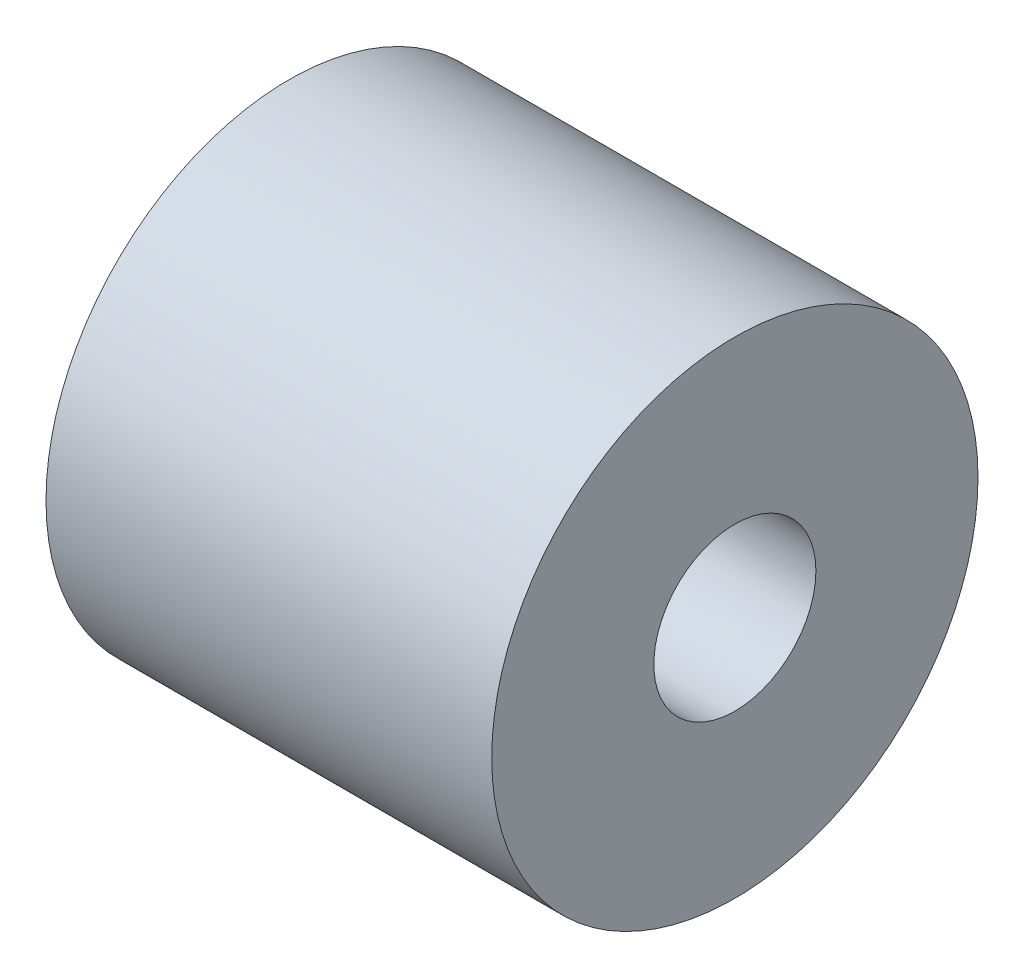
SolidWorks part; units mm, degrees
ref_plane "Plan de face" through (0, 0, 0) normal (0, 0, 1) x (1, 0, 0)
ref_plane "Plan de dessus" through (0, 0, 0) normal (0, 1, 0) x (1, 0, 0)
ref_plane "Plan de droite" through (0, 0, 0) normal (1, 0, 0) x (0, 0, -1)
sketch "Esquisse1" plane through (0, 0, 0) normal (1, 0, 0) x (0, 0, -1)
  arc A0 (2.9773, 0.3683) -> (2.9271, 0.6573) centre (0, 0) ccw
  arc A1 (2.1922, 2.048) -> (1.9817, 2.2523) centre (0, 0) ccw
  arc A2 (0.5698, 2.9454) -> (0.2794, 2.987) centre (0, 0) ccw
  arc A3 (-1.2703, 2.7178) -> (-1.5297, 2.5807) centre (0, 0) ccw
  arc A4 (-2.6252, 1.4521) -> (-2.7544, 1.1887) centre (0, 0) ccw
  arc A5 (-2.9773, -0.3683) -> (-2.9271, -0.6573) centre (0, 0) ccw
  arc A6 (-2.1922, -2.048) -> (-1.9817, -2.2523) centre (0, 0) ccw
  arc A7 (-0.5698, -2.9454) -> (-0.2794, -2.987) centre (0, 0) ccw
  arc A8 (1.2703, -2.7178) -> (1.5297, -2.5807) centre (0, 0) ccw
  arc A9 (2.6252, -1.4521) -> (2.7544, -1.1887) centre (0, 0) ccw
  arc A10 (1.8368, -0.3764) -> (1.8687, -0.154) centre (0, 0) ccw
  arc A11 (1.7073, 0.7751) -> (1.6023, 0.9738) centre (0, 0) ccw
  arc A12 (0.9256, 1.6306) -> (0.7239, 1.7296) centre (0, 0) ccw
  arc A13 (-0.2096, 1.8632) -> (-0.431, 1.8248) centre (0, 0) ccw
  arc A14 (-1.2648, 1.3842) -> (-1.4213, 1.2229) centre (0, 0) ccw
  arc A15 (-1.8368, 0.3764) -> (-1.8687, 0.154) centre (0, 0) ccw
  arc A16 (-1.7073, -0.7751) -> (-1.6023, -0.9738) centre (0, 0) ccw
  arc A17 (-0.9256, -1.6306) -> (-0.7239, -1.7296) centre (0, 0) ccw
  arc A18 (0.2096, -1.8632) -> (0.431, -1.8248) centre (0, 0) ccw
  arc A19 (1.2648, -1.3842) -> (1.4213, -1.2229) centre (0, 0) ccw
  circle A20 centre (0, 0) radius 1
  spline S0 degree 3 poles (2.349, 0) (2.3611, 0) (2.4126, 0.0085) (2.4945, 0.0326) (2.6584, 0.1065) (2.823, 0.2207) (2.9394, 0.3292) (2.9773, 0.3683) knots 0 0 0 0 0.036251 0.155621 0.255291 0.575255 0.744085 0.744085 0.744085 0.744085
  spline S1 degree 3 poles (2.2114, 0.7921) (2.2228, 0.7962) (2.2741, 0.8056) (2.3594, 0.8105) (2.5386, 0.7962) (2.7321, 0.7442) (2.8782, 0.6813) (2.9271, 0.6573) knots 0 0 0 0 0.036251 0.155621 0.255291 0.575255 0.744085 0.744085 0.744085 0.744085
  spline S2 degree 3 poles (1.9004, 1.3807) (1.9102, 1.3878) (1.9469, 1.4249) (1.9989, 1.4926) (2.0881, 1.6487) (2.1541, 1.8379) (2.1845, 1.9941) (2.1922, 2.048) knots 0 0 0 0 0.036251 0.155621 0.255291 0.575255 0.744085 0.744085 0.744085 0.744085
  spline S3 degree 3 poles (1.3235, 1.9407) (1.3303, 1.9507) (1.3663, 1.9885) (1.4324, 2.0425) (1.5858, 2.1363) (1.7728, 2.2079) (1.9281, 2.243) (1.9817, 2.2523) knots 0 0 0 0 0.036251 0.155621 0.255291 0.575255 0.744085 0.744085 0.744085 0.744085
  spline S4 degree 3 poles (0.7259, 2.234) (0.7296, 2.2455) (0.7375, 2.2971) (0.7398, 2.3825) (0.7202, 2.5612) (0.6625, 2.753) (0.5952, 2.8973) (0.5698, 2.9454) knots 0 0 0 0 0.036251 0.155621 0.255291 0.575255 0.744085 0.744085 0.744085 0.744085
  spline S5 degree 3 poles (-0.07, 2.348) (-0.0704, 2.36) (-0.0634, 2.4118) (-0.0417, 2.4943) (0.0272, 2.6604) (0.1365, 2.8283) (0.2415, 2.9479) (0.2794, 2.987) knots 0 0 0 0 0.036251 0.155621 0.255291 0.575255 0.744085 0.744085 0.744085 0.744085
  spline S6 degree 3 poles (-0.7259, 2.234) (-0.7296, 2.2455) (-0.7536, 2.2919) (-0.8019, 2.3623) (-0.9228, 2.4954) (-1.0823, 2.6166) (-1.2215, 2.6938) (-1.2703, 2.7178) knots 0 0 0 0 0.036251 0.155621 0.255291 0.575255 0.744085 0.744085 0.744085 0.744085
  spline S7 degree 3 poles (-1.4367, 1.8584) (-1.4441, 1.8679) (-1.4689, 1.9139) (-1.4999, 1.9934) (-1.5417, 2.1683) (-1.552, 2.3684) (-1.5374, 2.5268) (-1.5297, 2.5807) knots 0 0 0 0 0.036251 0.155621 0.255291 0.575255 0.744085 0.744085 0.744085 0.744085
  spline S8 degree 3 poles (-1.9004, 1.3807) (-1.9102, 1.3878) (-1.9568, 1.4112) (-2.0373, 1.4398) (-2.2133, 1.4764) (-2.4136, 1.4808) (-2.5715, 1.4614) (-2.6252, 1.4521) knots 0 0 0 0 0.036251 0.155621 0.255291 0.575255 0.744085 0.744085 0.744085 0.744085
  spline S9 degree 3 poles (-2.2547, 0.659) (-2.2663, 0.6624) (-2.3133, 0.6849) (-2.3852, 0.7311) (-2.5218, 0.848) (-2.6477, 1.0038) (-2.729, 1.1406) (-2.7544, 1.1887) knots 0 0 0 0 0.036251 0.155621 0.255291 0.575255 0.744085 0.744085 0.744085 0.744085
  spline S10 degree 3 poles (-2.349, 0) (-2.3611, 0) (-2.4126, -0.0085) (-2.4945, -0.0326) (-2.6584, -0.1065) (-2.823, -0.2207) (-2.9394, -0.3292) (-2.9773, -0.3683) knots 0 0 0 0 0.036251 0.155621 0.255291 0.575255 0.744085 0.744085 0.744085 0.744085
  spline S11 degree 3 poles (-2.2114, -0.7921) (-2.2228, -0.7962) (-2.2741, -0.8056) (-2.3594, -0.8105) (-2.5386, -0.7962) (-2.7321, -0.7442) (-2.8782, -0.6813) (-2.9271, -0.6573) knots 0 0 0 0 0.036251 0.155621 0.255291 0.575255 0.744085 0.744085 0.744085 0.744085
  spline S12 degree 3 poles (-1.9004, -1.3807) (-1.9102, -1.3878) (-1.9469, -1.4249) (-1.9989, -1.4926) (-2.0881, -1.6487) (-2.1541, -1.8379) (-2.1845, -1.9941) (-2.1922, -2.048) knots 0 0 0 0 0.036251 0.155621 0.255291 0.575255 0.744085 0.744085 0.744085 0.744085
  spline S13 degree 3 poles (-1.3235, -1.9407) (-1.3303, -1.9507) (-1.3663, -1.9885) (-1.4324, -2.0425) (-1.5858, -2.1363) (-1.7728, -2.2079) (-1.9281, -2.243) (-1.9817, -2.2523) knots 0 0 0 0 0.036251 0.155621 0.255291 0.575255 0.744085 0.744085 0.744085 0.744085
  spline S14 degree 3 poles (-0.7259, -2.234) (-0.7296, -2.2455) (-0.7375, -2.2971) (-0.7398, -2.3825) (-0.7202, -2.5612) (-0.6625, -2.753) (-0.5952, -2.8973) (-0.5698, -2.9454) knots 0 0 0 0 0.036251 0.155621 0.255291 0.575255 0.744085 0.744085 0.744085 0.744085
  spline S15 degree 3 poles (0.07, -2.348) (0.0704, -2.36) (0.0634, -2.4118) (0.0417, -2.4943) (-0.0272, -2.6604) (-0.1365, -2.8283) (-0.2415, -2.9479) (-0.2794, -2.987) knots 0 0 0 0 0.036251 0.155621 0.255291 0.575255 0.744085 0.744085 0.744085 0.744085
  spline S16 degree 3 poles (0.7259, -2.234) (0.7296, -2.2455) (0.7536, -2.2919) (0.8019, -2.3623) (0.9228, -2.4954) (1.0823, -2.6166) (1.2215, -2.6938) (1.2703, -2.7178) knots 0 0 0 0 0.036251 0.155621 0.255291 0.575255 0.744085 0.744085 0.744085 0.744085
  spline S17 degree 3 poles (1.4367, -1.8584) (1.4441, -1.8679) (1.4689, -1.9139) (1.4999, -1.9934) (1.5417, -2.1683) (1.552, -2.3684) (1.5374, -2.5268) (1.5297, -2.5807) knots 0 0 0 0 0.036251 0.155621 0.255291 0.575255 0.744085 0.744085 0.744085 0.744085
  spline S18 degree 3 poles (1.9004, -1.3807) (1.9102, -1.3878) (1.9568, -1.4112) (2.0373, -1.4398) (2.2133, -1.4764) (2.4136, -1.4808) (2.5715, -1.4614) (2.6252, -1.4521) knots 0 0 0 0 0.036251 0.155621 0.255291 0.575255 0.744085 0.744085 0.744085 0.744085
  spline S19 degree 3 poles (2.2547, -0.659) (2.2663, -0.6624) (2.3133, -0.6849) (2.3852, -0.7311) (2.5218, -0.848) (2.6477, -1.0038) (2.729, -1.1406) (2.7544, -1.1887) knots 0 0 0 0 0.036251 0.155621 0.255291 0.575255 0.744085 0.744085 0.744085 0.744085
  spline S20 degree 3 poles (2.349, 0) (2.2648, 0) (2.1034, 0.0291) (1.8817, -0.0633) (1.8687, -0.154) knots 0 0 0 0 0.252618 0.527509 0.527509 0.527509 0.527509
  spline S21 degree 3 poles (2.2547, -0.659) (2.1739, -0.6353) (2.0108, -0.618) (1.8238, -0.4671) (1.8368, -0.3764) knots 0 0 0 0 0.252618 0.527509 0.527509 0.527509 0.527509
  spline S22 degree 3 poles (1.9004, 1.3807) (1.8323, 1.3312) (1.6846, 1.2599) (1.5595, 1.0548) (1.6023, 0.9738) knots 0 0 0 0 0.252618 0.527509 0.527509 0.527509 0.527509
  spline S23 degree 3 poles (2.2114, 0.7921) (2.1321, 0.7637) (1.99, 0.682) (1.7501, 0.6941) (1.7073, 0.7751) knots 0 0 0 0 0.252618 0.527509 0.527509 0.527509 0.527509
  spline S24 degree 3 poles (0.7259, 2.234) (0.6999, 2.1539) (0.6223, 2.0095) (0.6416, 1.77) (0.7239, 1.7296) knots 0 0 0 0 0.252618 0.527509 0.527509 0.527509 0.527509
  spline S25 degree 3 poles (1.3235, 1.9407) (1.276, 1.8711) (1.2091, 1.7214) (1.0079, 1.5902) (0.9256, 1.6306) knots 0 0 0 0 0.252618 0.527509 0.527509 0.527509 0.527509
  spline S26 degree 3 poles (-0.7259, 2.234) (-0.6999, 2.1539) (-0.6776, 1.9915) (-0.5213, 1.8091) (-0.431, 1.8248) knots 0 0 0 0 0.252618 0.527509 0.527509 0.527509 0.527509
  spline S27 degree 3 poles (-0.07, 2.348) (-0.0675, 2.2638) (-0.0336, 2.1034) (-0.1193, 1.8789) (-0.2096, 1.8632) knots 0 0 0 0 0.252618 0.527509 0.527509 0.527509 0.527509
  spline S28 degree 3 poles (-1.9004, 1.3807) (-1.8323, 1.3312) (-1.7188, 1.2128) (-1.4851, 1.1572) (-1.4213, 1.2229) knots 0 0 0 0 0.252618 0.527509 0.527509 0.527509 0.527509
  spline S29 degree 3 poles (-1.4367, 1.8584) (-1.3852, 1.7918) (-1.2635, 1.6819) (-1.2009, 1.4499) (-1.2648, 1.3842) knots 0 0 0 0 0.252618 0.527509 0.527509 0.527509 0.527509
  spline S30 degree 3 poles (-2.349, 0) (-2.2648, 0) (-2.1034, -0.0291) (-1.8817, 0.0633) (-1.8687, 0.154) knots 0 0 0 0 0.252618 0.527509 0.527509 0.527509 0.527509
  spline S31 degree 3 poles (-2.2547, 0.659) (-2.1739, 0.6353) (-2.0108, 0.618) (-1.8238, 0.4671) (-1.8368, 0.3764) knots 0 0 0 0 0.252618 0.527509 0.527509 0.527509 0.527509
  spline S32 degree 3 poles (-1.9004, -1.3807) (-1.8323, -1.3312) (-1.6846, -1.2599) (-1.5595, -1.0548) (-1.6023, -0.9738) knots 0 0 0 0 0.252618 0.527509 0.527509 0.527509 0.527509
  spline S33 degree 3 poles (-2.2114, -0.7921) (-2.1321, -0.7637) (-1.99, -0.682) (-1.7501, -0.6941) (-1.7073, -0.7751) knots 0 0 0 0 0.252618 0.527509 0.527509 0.527509 0.527509
  spline S34 degree 3 poles (-0.7259, -2.234) (-0.6999, -2.1539) (-0.6223, -2.0095) (-0.6416, -1.77) (-0.7239, -1.7296) knots 0 0 0 0 0.252618 0.527509 0.527509 0.527509 0.527509
  spline S35 degree 3 poles (-1.3235, -1.9407) (-1.276, -1.8711) (-1.2091, -1.7214) (-1.0079, -1.5902) (-0.9256, -1.6306) knots 0 0 0 0 0.252618 0.527509 0.527509 0.527509 0.527509
  spline S36 degree 3 poles (0.7259, -2.234) (0.6999, -2.1539) (0.6776, -1.9915) (0.5213, -1.8091) (0.431, -1.8248) knots 0 0 0 0 0.252618 0.527509 0.527509 0.527509 0.527509
  spline S37 degree 3 poles (0.07, -2.348) (0.0675, -2.2638) (0.0336, -2.1034) (0.1193, -1.8789) (0.2096, -1.8632) knots 0 0 0 0 0.252618 0.527509 0.527509 0.527509 0.527509
  spline S38 degree 3 poles (1.9004, -1.3807) (1.8323, -1.3312) (1.7188, -1.2128) (1.4851, -1.1572) (1.4213, -1.2229) knots 0 0 0 0 0.252618 0.527509 0.527509 0.527509 0.527509
  spline S39 degree 3 poles (1.4367, -1.8584) (1.3852, -1.7918) (1.2635, -1.6819) (1.2009, -1.4499) (1.2648, -1.3842) knots 0 0 0 0 0.252618 0.527509 0.527509 0.527509 0.527509
  dimension "D1" = 2
extrude "Boss.-Extru.1" add sketch "Esquisse1" along normal blind 5.5
sketch "Esquisse2" plane through (5.5, 0, 0) normal (1, 0, 0) x (0, 0, -1)
  circle A0 centre (0, 0) radius 3
  circle A1 centre (0, 0) radius 1
extrude "Boss.-Extru.2" add sketch "Esquisse2" against normal up to surface (5.5 mm away) up to face at (0, 0, 0)
